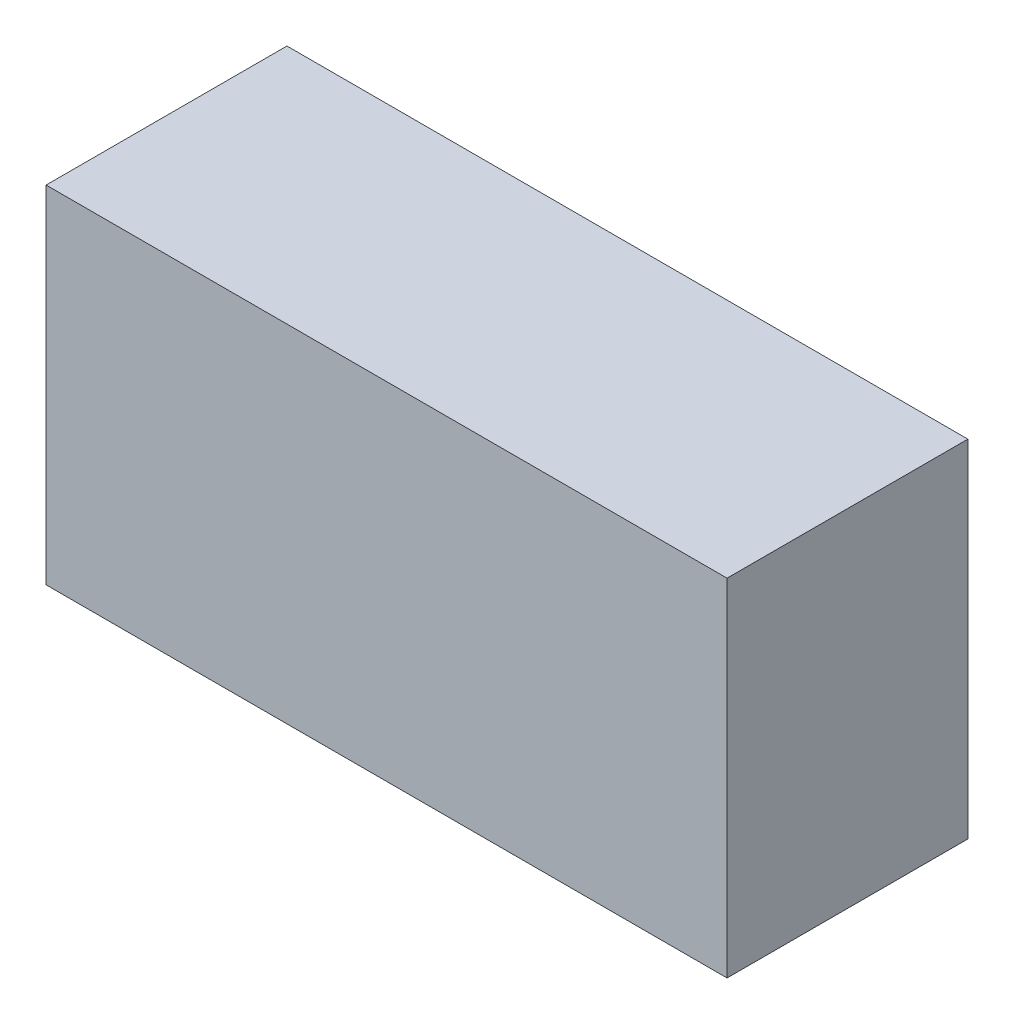
SolidWorks part; units mm, degrees
ref_plane "Front Plane" through (0, 0, 0) normal (0, 0, 1) x (1, 0, 0)
ref_plane "Top Plane" through (0, 0, 0) normal (0, 1, 0) x (1, 0, 0)
ref_plane "Right Plane" through (0, 0, 0) normal (1, 0, 0) x (0, 0, -1)
sketch "Sketch1" plane through (0, 0, 0) normal (0, 1, 0) x (1, 0, 0)
  line L1 (0, 0) -> (82, 0)
  line L2 (0, 0) -> (0, 29)
  line L3 (0, 29) -> (82, 29)
  line L4 (82, 0) -> (82, 29)
  dimension "D1" = 82
  dimension "D2" = 29
extrude "Boss-Extrude1" add sketch "Sketch1" along normal blind 41.7
